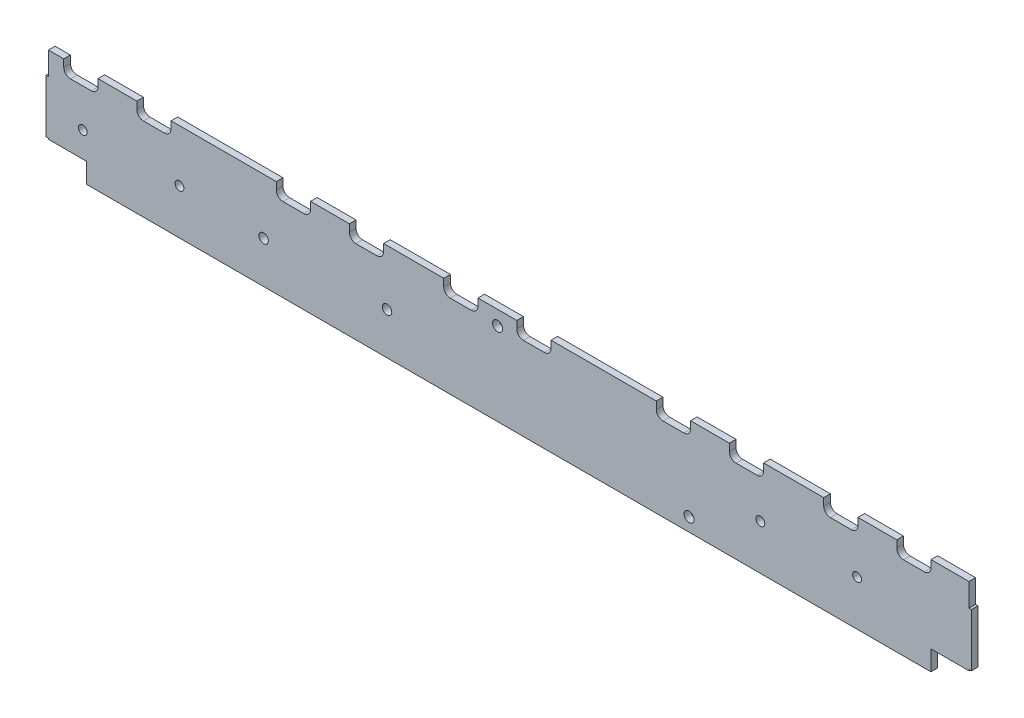
SolidWorks part; units mm, degrees
material "PP Film"
ref_plane "X-Y Datum" through (0, 0, 0) normal (0, 0, 1) x (1, 0, 0)
ref_plane "X-Z Datum" through (0, 0, 0) normal (0, 1, 0) x (1, 0, 0)
ref_plane "Y-Z Datum" through (0, 0, 0) normal (1, 0, 0) x (0, 0, -1)
sketch "Sketch2" plane through (0, 0, 0) normal (0, 0, 1) x (1, 0, 0)
  line L0 (-166.3768, -167.122) -> (-166.3768, -157.216)
  line L1 (-167.5198, -193.665) -> (-167.5198, -187.315)
  line L2 (273.6032, -167.122) -> (273.6032, -157.216)
  line L3 (-163.0588, -174.615) -> (-163.0588, -187.315)
  line L4 (274.7462, -174.615) -> (274.7462, -168.265)
  line L5 (270.2852, -174.615) -> (270.2852, -187.315)
  line L64 (255.4262, -203.714) -> (255.4262, -194.181)
  line L65 (255.4262, -194.181) -> (273.6032, -194.181)
  line L66 (275.7462, -167.122) -> (275.7462, -157.216)
  line L67 (255.4262, -194.181) -> (273.6032, -194.181)
  line L68 (273.6032, -194.181) -> (273.6032, -193.665)
  line L69 (273.6032, -193.665) -> (274.7462, -193.665)
  line L70 (274.7462, -193.665) -> (274.7462, -168.265)
  line L71 (274.7462, -168.265) -> (273.6032, -168.265)
  line L72 (273.6032, -168.265) -> (273.6032, -167.122)
  line L73 (273.6032, -167.122) -> (275.7462, -167.122)
  line L74 (-166.3768, -194.181) -> (-148.1998, -194.181)
  line L75 (275.7462, -157.216) -> (255.4633, -157.216)
  line L76 (255.4633, -157.216) -> (255.4633, -160.708)
  line L77 (252.2883, -163.883) -> (242.2883, -163.883)
  line L78 (239.1133, -160.708) -> (239.1133, -157.216)
  line L79 (239.1133, -157.216) -> (220.5383, -157.216)
  line L80 (220.5383, -157.216) -> (220.5383, -160.708)
  line L81 (217.3633, -163.883) -> (207.3633, -163.883)
  line L82 (204.1883, -160.708) -> (204.1883, -157.216)
  line L83 (204.1883, -157.216) -> (175.4521, -157.216)
  line L84 (175.4521, -157.216) -> (175.4521, -160.708)
  line L85 (172.2771, -163.883) -> (162.2771, -163.883)
  line L86 (159.1021, -160.708) -> (159.1021, -157.216)
  line L87 (159.1021, -157.216) -> (140.5271, -157.216)
  line L88 (140.5271, -157.216) -> (140.5271, -160.708)
  line L89 (137.3521, -163.883) -> (127.3521, -163.883)
  line L90 (124.1771, -160.708) -> (124.1771, -157.216)
  line L91 (124.1771, -157.216) -> (73.8493, -157.216)
  line L92 (73.8493, -157.216) -> (73.8493, -160.708)
  line L93 (70.6743, -163.883) -> (60.6743, -163.883)
  line L94 (57.4993, -160.708) -> (57.4993, -157.216)
  line L95 (57.4993, -157.216) -> (38.9243, -157.216)
  line L96 (38.9243, -157.216) -> (38.9243, -160.708)
  line L97 (35.7493, -163.883) -> (25.7493, -163.883)
  line L98 (22.5743, -160.708) -> (22.5743, -157.216)
  line L99 (22.5743, -157.216) -> (-6.1619, -157.216)
  line L100 (-6.1619, -157.216) -> (-6.1619, -160.708)
  line L101 (-9.3369, -163.883) -> (-19.3369, -163.883)
  line L102 (-22.5119, -160.708) -> (-22.5119, -157.216)
  line L103 (-22.5119, -157.216) -> (-41.0869, -157.216)
  line L104 (-41.0869, -157.216) -> (-41.0869, -160.708)
  line L105 (-44.2619, -163.883) -> (-54.2619, -163.883)
  line L106 (-57.4369, -160.708) -> (-57.4369, -157.216)
  line L107 (-57.4369, -157.216) -> (-107.7647, -157.216)
  line L108 (-107.7647, -157.216) -> (-107.7647, -160.708)
  line L109 (-110.9397, -163.883) -> (-120.9397, -163.883)
  line L110 (-124.1147, -160.708) -> (-124.1147, -157.216)
  line L111 (-124.1147, -157.216) -> (-142.6897, -157.216)
  line L112 (-142.6897, -157.216) -> (-142.6897, -160.708)
  line L113 (-145.8647, -163.883) -> (-155.8647, -163.883)
  line L114 (-159.0397, -160.708) -> (-159.0397, -157.216)
  line L115 (-159.0397, -157.216) -> (-168.5198, -157.216)
  line L116 (-168.5198, -157.216) -> (-168.5198, -167.122)
  line L117 (-168.5198, -167.122) -> (-166.3768, -167.122)
  line L118 (-166.3768, -167.122) -> (-166.3768, -168.265)
  line L119 (-166.3768, -168.265) -> (-167.5198, -168.265)
  line L120 (-167.5198, -168.265) -> (-167.5198, -193.665)
  line L121 (-167.5198, -193.665) -> (-166.3768, -193.665)
  line L122 (-166.3768, -193.665) -> (-166.3768, -194.181)
  line L123 (-166.3768, -194.181) -> (-148.1998, -194.181)
  line L126 (-148.1998, -194.181) -> (-148.1998, -203.714)
  line L127 (-148.1998, -203.714) -> (255.4262, -203.714)
  line L128 (255.4262, -203.714) -> (255.4262, -194.181)
  line L130 (275.7462, -167.122) -> (275.7462, -157.216)
  line L132 (273.6032, -194.181) -> (273.6032, -193.665)
  line L133 (273.6032, -193.665) -> (274.7462, -193.665)
  line L134 (274.7462, -193.665) -> (274.7462, -168.265)
  line L135 (274.7462, -168.265) -> (273.6032, -168.265)
  line L136 (273.6032, -168.265) -> (273.6032, -167.122)
  line L137 (273.6032, -167.122) -> (275.7462, -167.122)
  line L139 (275.7462, -157.216) -> (255.4633, -157.216)
  line L140 (255.4633, -157.216) -> (255.4633, -160.708)
  line L141 (252.2883, -163.883) -> (242.2883, -163.883)
  line L142 (239.1133, -160.708) -> (239.1133, -157.216)
  line L143 (239.1133, -157.216) -> (220.5383, -157.216)
  line L144 (220.5383, -157.216) -> (220.5383, -160.708)
  line L145 (217.3633, -163.883) -> (207.3633, -163.883)
  line L146 (204.1883, -160.708) -> (204.1883, -157.216)
  line L147 (204.1883, -157.216) -> (175.4521, -157.216)
  line L148 (175.4521, -157.216) -> (175.4521, -160.708)
  line L149 (172.2771, -163.883) -> (162.2771, -163.883)
  line L150 (159.1021, -160.708) -> (159.1021, -157.216)
  line L151 (159.1021, -157.216) -> (140.5271, -157.216)
  line L152 (140.5271, -157.216) -> (140.5271, -160.708)
  line L153 (137.3521, -163.883) -> (127.3521, -163.883)
  line L154 (124.1771, -160.708) -> (124.1771, -157.216)
  line L155 (124.1771, -157.216) -> (73.8493, -157.216)
  line L156 (73.8493, -157.216) -> (73.8493, -160.708)
  line L157 (70.6743, -163.883) -> (60.6743, -163.883)
  line L158 (57.4993, -160.708) -> (57.4993, -157.216)
  line L159 (57.4993, -157.216) -> (38.9243, -157.216)
  line L160 (38.9243, -157.216) -> (38.9243, -160.708)
  line L161 (35.7493, -163.883) -> (25.7493, -163.883)
  line L162 (22.5743, -160.708) -> (22.5743, -157.216)
  line L163 (22.5743, -157.216) -> (-6.1619, -157.216)
  line L164 (-6.1619, -157.216) -> (-6.1619, -160.708)
  line L165 (-9.3369, -163.883) -> (-19.3369, -163.883)
  line L166 (-22.5119, -160.708) -> (-22.5119, -157.216)
  line L167 (-22.5119, -157.216) -> (-41.0869, -157.216)
  line L168 (-41.0869, -157.216) -> (-41.0869, -160.708)
  line L169 (-44.2619, -163.883) -> (-54.2619, -163.883)
  line L170 (-57.4369, -160.708) -> (-57.4369, -157.216)
  line L171 (-57.4369, -157.216) -> (-107.7647, -157.216)
  line L172 (-107.7647, -157.216) -> (-107.7647, -160.708)
  line L173 (-110.9397, -163.883) -> (-120.9397, -163.883)
  line L174 (-124.1147, -160.708) -> (-124.1147, -157.216)
  line L175 (-124.1147, -157.216) -> (-142.6897, -157.216)
  line L176 (-142.6897, -157.216) -> (-142.6897, -160.708)
  line L177 (-145.8647, -163.883) -> (-155.8647, -163.883)
  line L178 (-159.0397, -160.708) -> (-159.0397, -157.216)
  line L179 (-159.0397, -157.216) -> (-168.5198, -157.216)
  line L180 (-168.5198, -157.216) -> (-168.5198, -167.122)
  line L181 (-168.5198, -167.122) -> (-166.3768, -167.122)
  line L182 (-166.3768, -167.122) -> (-166.3768, -168.265)
  line L183 (-166.3768, -168.265) -> (-167.5198, -168.265)
  line L184 (-167.5198, -168.265) -> (-167.5198, -193.665)
  line L185 (-167.5198, -193.665) -> (-166.3768, -193.665)
  line L186 (-166.3768, -193.665) -> (-166.3768, -194.181)
  line L190 (-148.1998, -194.181) -> (-148.1998, -203.714)
  line L191 (-148.1998, -203.714) -> (255.4262, -203.714)
  line L249 (255.4262, -194.181) -> (273.6032, -194.181)
  line L250 (273.6032, -194.181) -> (273.6032, -193.665)
  line L251 (273.6032, -193.665) -> (274.7462, -193.665)
  line L252 (274.7462, -193.665) -> (274.7462, -168.265)
  line L253 (274.7462, -168.265) -> (273.6032, -168.265)
  line L254 (273.6032, -168.265) -> (273.6032, -167.122)
  line L255 (273.6032, -167.122) -> (275.7462, -167.122)
  line L256 (275.7462, -167.122) -> (275.7462, -157.216)
  line L257 (275.7462, -157.216) -> (255.4633, -157.216)
  line L258 (255.4633, -157.216) -> (255.4633, -160.708)
  line L259 (252.2883, -163.883) -> (242.2883, -163.883)
  line L260 (239.1133, -160.708) -> (239.1133, -157.216)
  line L261 (239.1133, -157.216) -> (220.5383, -157.216)
  line L262 (220.5383, -157.216) -> (220.5383, -160.708)
  line L263 (217.3633, -163.883) -> (207.3633, -163.883)
  line L264 (204.1883, -160.708) -> (204.1883, -157.216)
  line L265 (204.1883, -157.216) -> (175.4521, -157.216)
  line L266 (175.4521, -157.216) -> (175.4521, -160.708)
  line L267 (172.2771, -163.883) -> (162.2771, -163.883)
  line L268 (159.1021, -160.708) -> (159.1021, -157.216)
  line L269 (159.1021, -157.216) -> (140.5271, -157.216)
  line L270 (140.5271, -157.216) -> (140.5271, -160.708)
  line L271 (137.3521, -163.883) -> (127.3521, -163.883)
  line L272 (124.1771, -160.708) -> (124.1771, -157.216)
  line L273 (124.1771, -157.216) -> (73.8493, -157.216)
  line L274 (73.8493, -157.216) -> (73.8493, -160.708)
  line L275 (70.6743, -163.883) -> (60.6743, -163.883)
  line L276 (57.4993, -160.708) -> (57.4993, -157.216)
  line L277 (57.4993, -157.216) -> (38.9243, -157.216)
  line L278 (38.9243, -157.216) -> (38.9243, -160.708)
  line L279 (35.7493, -163.883) -> (25.7493, -163.883)
  line L280 (22.5743, -160.708) -> (22.5743, -157.216)
  line L281 (22.5743, -157.216) -> (-6.1619, -157.216)
  line L282 (-6.1619, -157.216) -> (-6.1619, -160.708)
  line L283 (-9.3369, -163.883) -> (-19.3369, -163.883)
  line L284 (-22.5119, -160.708) -> (-22.5119, -157.216)
  line L285 (-22.5119, -157.216) -> (-41.0869, -157.216)
  line L286 (-41.0869, -157.216) -> (-41.0869, -160.708)
  line L287 (-44.2619, -163.883) -> (-54.2619, -163.883)
  line L288 (-57.4369, -160.708) -> (-57.4369, -157.216)
  line L289 (-57.4369, -157.216) -> (-107.7647, -157.216)
  line L290 (-107.7647, -157.216) -> (-107.7647, -160.708)
  line L291 (-110.9397, -163.883) -> (-120.9397, -163.883)
  line L292 (-124.1147, -160.708) -> (-124.1147, -157.216)
  line L293 (-124.1147, -157.216) -> (-142.6897, -157.216)
  line L294 (-142.6897, -157.216) -> (-142.6897, -160.708)
  line L295 (-145.8647, -163.883) -> (-155.8647, -163.883)
  line L296 (-159.0397, -160.708) -> (-159.0397, -157.216)
  line L297 (-159.0397, -157.216) -> (-168.5198, -157.216)
  line L298 (-168.5198, -157.216) -> (-168.5198, -167.122)
  line L299 (-168.5198, -167.122) -> (-166.3768, -167.122)
  line L300 (-166.3768, -167.122) -> (-166.3768, -168.265)
  line L301 (-166.3768, -168.265) -> (-167.5198, -168.265)
  line L302 (-167.5198, -168.265) -> (-167.5198, -193.665)
  line L303 (-167.5198, -193.665) -> (-166.3768, -193.665)
  line L304 (-166.3768, -193.665) -> (-166.3768, -194.181)
  line L305 (-166.3768, -194.181) -> (-148.1998, -194.181)
  line L306 (-148.1998, -194.181) -> (-148.1998, -203.714)
  line L307 (-148.1998, -203.714) -> (255.4262, -203.714)
  line L308 (255.4262, -203.714) -> (255.4262, -194.181)
  line L309 (255.4262, -194.181) -> (273.6032, -194.181)
  line L310 (273.6032, -194.181) -> (273.6032, -193.665)
  line L311 (273.6032, -193.665) -> (274.7462, -193.665)
  line L312 (274.7462, -193.665) -> (274.7462, -168.265)
  line L313 (274.7462, -168.265) -> (273.6032, -168.265)
  line L314 (273.6032, -168.265) -> (273.6032, -167.122)
  line L315 (273.6032, -167.122) -> (275.7462, -167.122)
  line L316 (275.7462, -167.122) -> (275.7462, -157.216)
  line L317 (275.7462, -157.216) -> (255.4633, -157.216)
  line L318 (255.4633, -157.216) -> (255.4633, -160.708)
  line L319 (252.2883, -163.883) -> (242.2883, -163.883)
  line L320 (239.1133, -160.708) -> (239.1133, -157.216)
  line L321 (239.1133, -157.216) -> (220.5383, -157.216)
  line L322 (220.5383, -157.216) -> (220.5383, -160.708)
  line L323 (217.3633, -163.883) -> (207.3633, -163.883)
  line L324 (204.1883, -160.708) -> (204.1883, -157.216)
  line L325 (204.1883, -157.216) -> (175.4521, -157.216)
  line L326 (175.4521, -157.216) -> (175.4521, -160.708)
  line L327 (172.2771, -163.883) -> (162.2771, -163.883)
  line L328 (159.1021, -160.708) -> (159.1021, -157.216)
  line L329 (159.1021, -157.216) -> (140.5271, -157.216)
  line L330 (140.5271, -157.216) -> (140.5271, -160.708)
  line L331 (137.3521, -163.883) -> (127.3521, -163.883)
  line L332 (124.1771, -160.708) -> (124.1771, -157.216)
  line L333 (124.1771, -157.216) -> (73.8493, -157.216)
  line L334 (73.8493, -157.216) -> (73.8493, -160.708)
  line L335 (70.6743, -163.883) -> (60.6743, -163.883)
  line L336 (57.4993, -160.708) -> (57.4993, -157.216)
  line L337 (57.4993, -157.216) -> (38.9243, -157.216)
  line L338 (38.9243, -157.216) -> (38.9243, -160.708)
  line L339 (35.7493, -163.883) -> (25.7493, -163.883)
  line L340 (22.5743, -160.708) -> (22.5743, -157.216)
  line L341 (22.5743, -157.216) -> (-6.1619, -157.216)
  line L342 (-6.1619, -157.216) -> (-6.1619, -160.708)
  line L343 (-9.3369, -163.883) -> (-19.3369, -163.883)
  line L344 (-22.5119, -160.708) -> (-22.5119, -157.216)
  line L345 (-22.5119, -157.216) -> (-41.0869, -157.216)
  line L346 (-41.0869, -157.216) -> (-41.0869, -160.708)
  line L347 (-44.2619, -163.883) -> (-54.2619, -163.883)
  line L348 (-57.4369, -160.708) -> (-57.4369, -157.216)
  line L349 (-57.4369, -157.216) -> (-107.7647, -157.216)
  line L350 (-107.7647, -157.216) -> (-107.7647, -160.708)
  line L351 (-110.9397, -163.883) -> (-120.9397, -163.883)
  line L352 (-124.1147, -160.708) -> (-124.1147, -157.216)
  line L353 (-124.1147, -157.216) -> (-142.6897, -157.216)
  line L354 (-142.6897, -157.216) -> (-142.6897, -160.708)
  line L355 (-145.8647, -163.883) -> (-155.8647, -163.883)
  line L356 (-159.0397, -160.708) -> (-159.0397, -157.216)
  line L357 (-159.0397, -157.216) -> (-168.5198, -157.216)
  line L358 (-168.5198, -157.216) -> (-168.5198, -167.122)
  line L359 (-168.5198, -167.122) -> (-166.3768, -167.122)
  line L360 (-166.3768, -167.122) -> (-166.3768, -168.265)
  line L361 (-166.3768, -168.265) -> (-167.5198, -168.265)
  line L362 (-167.5198, -168.265) -> (-167.5198, -193.665)
  line L363 (-167.5198, -193.665) -> (-166.3768, -193.665)
  line L364 (-166.3768, -193.665) -> (-166.3768, -194.181)
  line L365 (-166.3768, -194.181) -> (-148.1998, -194.181)
  line L366 (-148.1998, -194.181) -> (-148.1998, -203.714)
  line L367 (-148.1998, -203.714) -> (255.4262, -203.714)
  line L368 (255.4262, -203.714) -> (255.4262, -194.181)
  arc A20 (252.2883, -163.883) -> (255.4633, -160.708) centre (252.2883, -160.708) ccw
  arc A21 (239.1133, -160.708) -> (242.2883, -163.883) centre (242.2883, -160.708) ccw
  arc A22 (217.3633, -163.883) -> (220.5383, -160.708) centre (217.3633, -160.708) ccw
  arc A23 (204.1883, -160.708) -> (207.3633, -163.883) centre (207.3633, -160.708) ccw
  arc A24 (172.2771, -163.883) -> (175.4521, -160.708) centre (172.2771, -160.708) ccw
  arc A25 (159.1021, -160.708) -> (162.2771, -163.883) centre (162.2771, -160.708) ccw
  arc A26 (137.3521, -163.883) -> (140.5271, -160.708) centre (137.3521, -160.708) ccw
  arc A27 (124.1771, -160.708) -> (127.3521, -163.883) centre (127.3521, -160.708) ccw
  arc A28 (70.6743, -163.883) -> (73.8493, -160.708) centre (70.6743, -160.708) ccw
  arc A29 (57.4993, -160.708) -> (60.6743, -163.883) centre (60.6743, -160.708) ccw
  arc A30 (35.7493, -163.883) -> (38.9243, -160.708) centre (35.7493, -160.708) ccw
  arc A31 (22.5743, -160.708) -> (25.7493, -163.883) centre (25.7493, -160.708) ccw
  arc A32 (-9.3369, -163.883) -> (-6.1619, -160.708) centre (-9.3369, -160.708) ccw
  arc A33 (-22.5119, -160.708) -> (-19.3369, -163.883) centre (-19.3369, -160.708) ccw
  arc A34 (-44.2619, -163.883) -> (-41.0869, -160.708) centre (-44.2619, -160.708) ccw
  arc A35 (-57.4369, -160.708) -> (-54.2619, -163.883) centre (-54.2619, -160.708) ccw
  arc A36 (-110.9397, -163.883) -> (-107.7647, -160.708) centre (-110.9397, -160.708) ccw
  arc A37 (-124.1147, -160.708) -> (-120.9397, -163.883) centre (-120.9397, -160.708) ccw
  arc A38 (-145.8647, -163.883) -> (-142.6897, -160.708) centre (-145.8647, -160.708) ccw
  arc A39 (-159.0397, -160.708) -> (-155.8647, -163.883) centre (-155.8647, -160.708) ccw
  arc A40 (252.2883, -163.883) -> (255.4633, -160.708) centre (252.2883, -160.708) ccw
  arc A41 (239.1133, -160.708) -> (242.2883, -163.883) centre (242.2883, -160.708) ccw
  arc A42 (217.3633, -163.883) -> (220.5383, -160.708) centre (217.3633, -160.708) ccw
  arc A43 (204.1883, -160.708) -> (207.3633, -163.883) centre (207.3633, -160.708) ccw
  arc A44 (172.2771, -163.883) -> (175.4521, -160.708) centre (172.2771, -160.708) ccw
  arc A45 (159.1021, -160.708) -> (162.2771, -163.883) centre (162.2771, -160.708) ccw
  arc A46 (137.3521, -163.883) -> (140.5271, -160.708) centre (137.3521, -160.708) ccw
  arc A47 (124.1771, -160.708) -> (127.3521, -163.883) centre (127.3521, -160.708) ccw
  arc A48 (70.6743, -163.883) -> (73.8493, -160.708) centre (70.6743, -160.708) ccw
  arc A49 (57.4993, -160.708) -> (60.6743, -163.883) centre (60.6743, -160.708) ccw
  arc A50 (35.7493, -163.883) -> (38.9243, -160.708) centre (35.7493, -160.708) ccw
  arc A51 (22.5743, -160.708) -> (25.7493, -163.883) centre (25.7493, -160.708) ccw
  arc A52 (-9.3369, -163.883) -> (-6.1619, -160.708) centre (-9.3369, -160.708) ccw
  arc A53 (-22.5119, -160.708) -> (-19.3369, -163.883) centre (-19.3369, -160.708) ccw
  arc A54 (-44.2619, -163.883) -> (-41.0869, -160.708) centre (-44.2619, -160.708) ccw
  arc A55 (-57.4369, -160.708) -> (-54.2619, -163.883) centre (-54.2619, -160.708) ccw
  arc A56 (-110.9397, -163.883) -> (-107.7647, -160.708) centre (-110.9397, -160.708) ccw
  arc A57 (-124.1147, -160.708) -> (-120.9397, -163.883) centre (-120.9397, -160.708) ccw
  arc A58 (-145.8647, -163.883) -> (-142.6897, -160.708) centre (-145.8647, -160.708) ccw
  arc A59 (-159.0397, -160.708) -> (-155.8647, -163.883) centre (-155.8647, -160.708) ccw
  arc A80 (252.2883, -163.883) -> (255.4633, -160.708) centre (252.2883, -160.708) ccw
  arc A81 (239.1133, -160.708) -> (242.2883, -163.883) centre (242.2883, -160.708) ccw
  arc A82 (217.3633, -163.883) -> (220.5383, -160.708) centre (217.3633, -160.708) ccw
  arc A83 (204.1883, -160.708) -> (207.3633, -163.883) centre (207.3633, -160.708) ccw
  arc A84 (172.2771, -163.883) -> (175.4521, -160.708) centre (172.2771, -160.708) ccw
  arc A85 (159.1021, -160.708) -> (162.2771, -163.883) centre (162.2771, -160.708) ccw
  arc A86 (137.3521, -163.883) -> (140.5271, -160.708) centre (137.3521, -160.708) ccw
  arc A87 (124.1771, -160.708) -> (127.3521, -163.883) centre (127.3521, -160.708) ccw
  arc A88 (70.6743, -163.883) -> (73.8493, -160.708) centre (70.6743, -160.708) ccw
  arc A89 (57.4993, -160.708) -> (60.6743, -163.883) centre (60.6743, -160.708) ccw
  arc A90 (35.7493, -163.883) -> (38.9243, -160.708) centre (35.7493, -160.708) ccw
  arc A91 (22.5743, -160.708) -> (25.7493, -163.883) centre (25.7493, -160.708) ccw
  arc A92 (-9.3369, -163.883) -> (-6.1619, -160.708) centre (-9.3369, -160.708) ccw
  arc A93 (-22.5119, -160.708) -> (-19.3369, -163.883) centre (-19.3369, -160.708) ccw
  arc A94 (-44.2619, -163.883) -> (-41.0869, -160.708) centre (-44.2619, -160.708) ccw
  arc A95 (-57.4369, -160.708) -> (-54.2619, -163.883) centre (-54.2619, -160.708) ccw
  arc A96 (-110.9397, -163.883) -> (-107.7647, -160.708) centre (-110.9397, -160.708) ccw
  arc A97 (-124.1147, -160.708) -> (-120.9397, -163.883) centre (-120.9397, -160.708) ccw
  arc A98 (-145.8647, -163.883) -> (-142.6897, -160.708) centre (-145.8647, -160.708) ccw
  arc A99 (-159.0397, -160.708) -> (-155.8647, -163.883) centre (-155.8647, -160.708) ccw
  arc A100 (252.2883, -163.883) -> (255.4633, -160.708) centre (252.2883, -160.708) ccw
  arc A101 (239.1133, -160.708) -> (242.2883, -163.883) centre (242.2883, -160.708) ccw
  arc A102 (217.3633, -163.883) -> (220.5383, -160.708) centre (217.3633, -160.708) ccw
  arc A103 (204.1883, -160.708) -> (207.3633, -163.883) centre (207.3633, -160.708) ccw
  arc A104 (172.2771, -163.883) -> (175.4521, -160.708) centre (172.2771, -160.708) ccw
  arc A105 (159.1021, -160.708) -> (162.2771, -163.883) centre (162.2771, -160.708) ccw
  arc A106 (137.3521, -163.883) -> (140.5271, -160.708) centre (137.3521, -160.708) ccw
  arc A107 (124.1771, -160.708) -> (127.3521, -163.883) centre (127.3521, -160.708) ccw
  arc A108 (70.6743, -163.883) -> (73.8493, -160.708) centre (70.6743, -160.708) ccw
  arc A109 (57.4993, -160.708) -> (60.6743, -163.883) centre (60.6743, -160.708) ccw
  arc A110 (35.7493, -163.883) -> (38.9243, -160.708) centre (35.7493, -160.708) ccw
  arc A111 (22.5743, -160.708) -> (25.7493, -163.883) centre (25.7493, -160.708) ccw
  arc A112 (-9.3369, -163.883) -> (-6.1619, -160.708) centre (-9.3369, -160.708) ccw
  arc A113 (-22.5119, -160.708) -> (-19.3369, -163.883) centre (-19.3369, -160.708) ccw
  arc A114 (-44.2619, -163.883) -> (-41.0869, -160.708) centre (-44.2619, -160.708) ccw
  arc A115 (-57.4369, -160.708) -> (-54.2619, -163.883) centre (-54.2619, -160.708) ccw
  arc A116 (-110.9397, -163.883) -> (-107.7647, -160.708) centre (-110.9397, -160.708) ccw
  arc A117 (-124.1147, -160.708) -> (-120.9397, -163.883) centre (-120.9397, -160.708) ccw
  arc A118 (-145.8647, -163.883) -> (-142.6897, -160.708) centre (-145.8647, -160.708) ccw
  arc A119 (-159.0397, -160.708) -> (-155.8647, -163.883) centre (-155.8647, -160.708) ccw
  dimension "D1" = 0
  dimension "D2" = 0
extrude "Boss-Extrude1" add sketch "Sketch2" along normal blind 3.175
sketch "Sketch4" plane through (0, 0, 3.175) normal (0, 0, 1) x (1, 0, 0)
  circle A0 centre (220.1062, -182.1047) radius 2.1 construction
  circle A1 centre (173.9062, -182.1047) radius 2.1 construction
  circle A4 centre (-4.5198, -183.714) radius 2.25 construction
  circle A5 centre (-63.5198, -183.714) radius 2.25 construction
  circle A6 centre (-103.7233, -182.1047) radius 2.1 construction
  circle A7 centre (-149.9233, -182.1047) radius 2.1 construction
  circle A8 centre (220.1062, -182.1047) radius 2.1
  circle A9 centre (173.9062, -182.1047) radius 2.1
  circle A12 centre (-4.5198, -183.714) radius 2.25
  circle A13 centre (-63.5198, -183.714) radius 2.25
  circle A14 centre (-103.7233, -182.1047) radius 2.1
  circle A15 centre (-149.9233, -182.1047) radius 2.1
  circle A16 centre (48.3181, -164.1047) radius 2.4 construction
  circle A17 centre (48.3181, -164.1047) radius 2.4
  circle A22 centre (139.8181, -197.3292) radius 2.4 construction
  circle A23 centre (139.8181, -197.3292) radius 2.4
  point P24 (0, 0)
extrude "Cut-Extrude2" cut sketch "Sketch4" against normal through all
